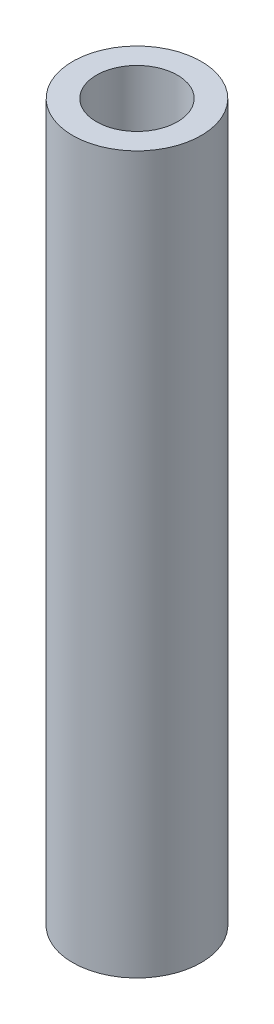
SolidWorks part; units mm, degrees
ref_plane "Front Plane" through (0, 0, 0) normal (0, 0, 1) x (1, 0, 0)
ref_plane "Top Plane" through (0, 0, 0) normal (0, 1, 0) x (1, 0, 0)
ref_plane "Right Plane" through (0, 0, 0) normal (1, 0, 0) x (0, 0, -1)
sketch "Sketch1" plane through (0, 0, 0) normal (0, 1, 0) x (1, 0, 0)
  circle A0 centre (0, 0) radius 3.175
  circle A1 centre (0, 0) radius 2
  dimension "D1" = 4
  dimension "D2" = 6.35
extrude "Boss-Extrude1" add sketch "Sketch1" along normal mid plane 35.4 contours A0 A1
